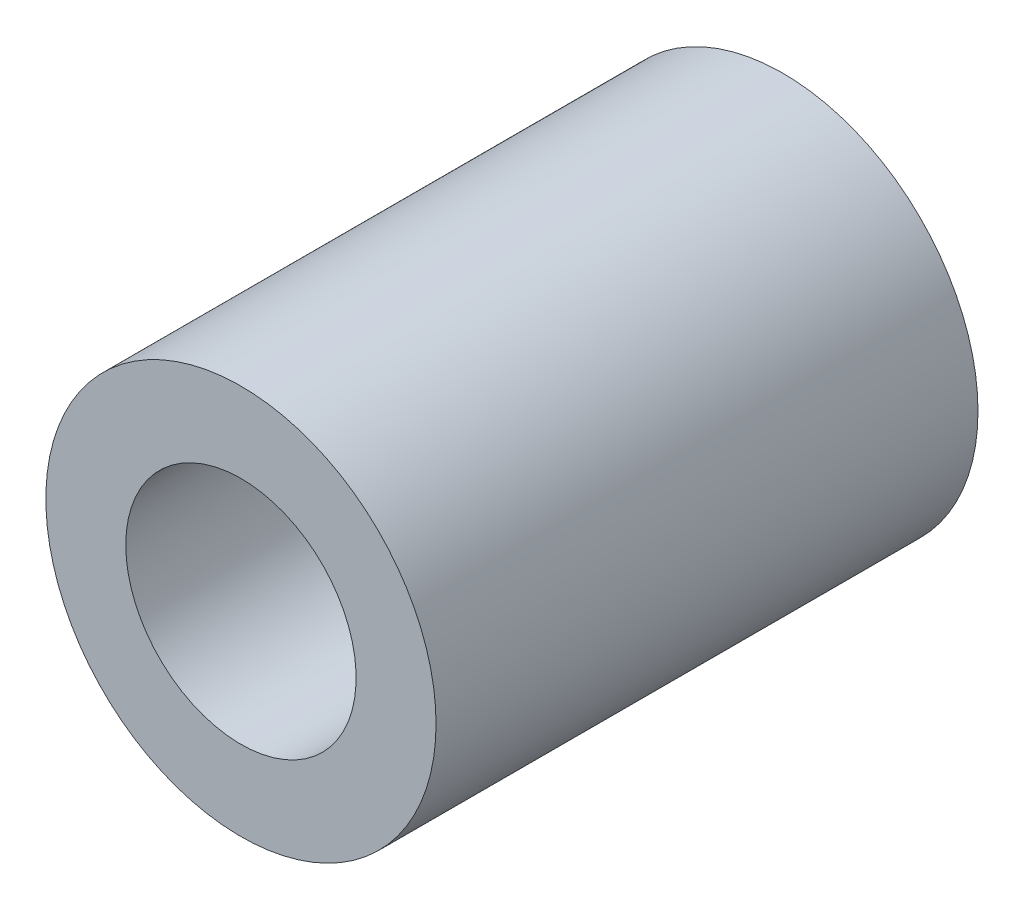
SolidWorks part; units mm, degrees
ref_plane "Front Plane" through (0, 0, 0) normal (0, 0, 1) x (1, 0, 0)
ref_plane "Top Plane" through (0, 0, 0) normal (0, 1, 0) x (1, 0, 0)
ref_plane "Right Plane" through (0, 0, 0) normal (1, 0, 0) x (0, 0, -1)
sketch "Sketch1" plane through (0, 0, 0) normal (0, 0, 1) x (1, 0, 0)
  circle A0 centre (0, 0) radius 3.6
  dimension "D1" = 7.2
extrude "Boss-Extrude1" add sketch "Sketch1" along normal blind 10 contours A0
sketch "Sketch2" plane through (0, 0, 0) normal (0, 0, -1) x (-1, 0, 0)
  circle A0 centre (0, 0) radius 2.125
  dimension "D1" = 4.25
extrude "Cut-Extrude1" cut sketch "Sketch2" against normal through all
